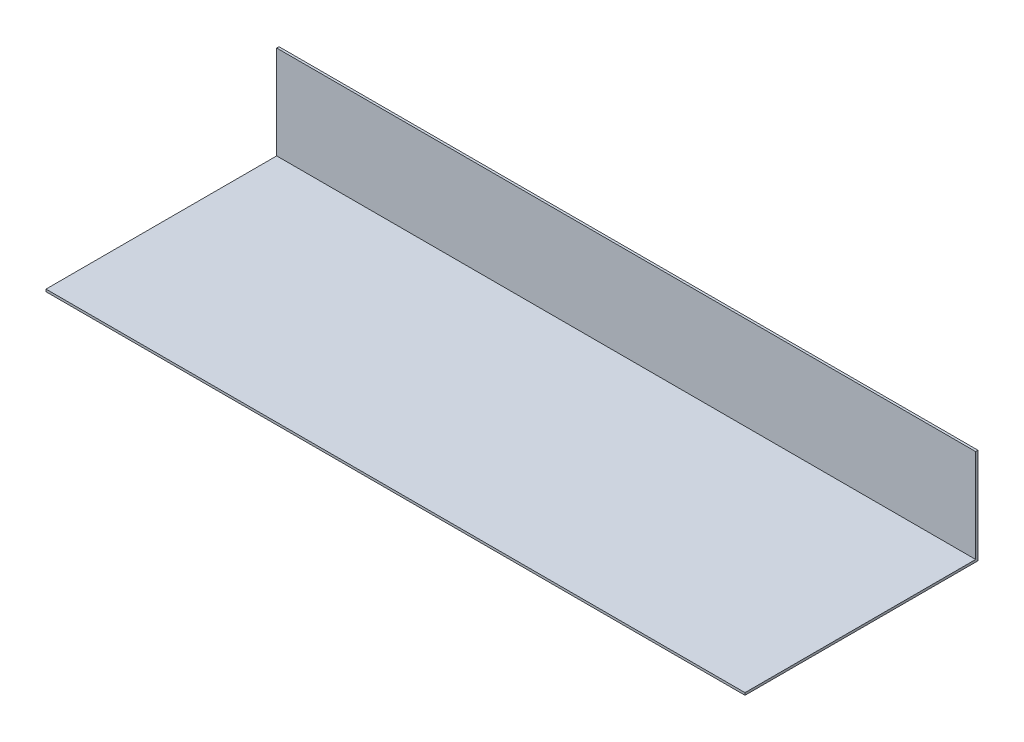
SolidWorks part; units mm, degrees
ref_plane "Front Plane" through (0, 0, 0) normal (0, 0, 1) x (1, 0, 0)
ref_plane "Top Plane" through (0, 0, 0) normal (0, 1, 0) x (1, 0, 0)
ref_plane "Right Plane" through (0, 0, 0) normal (1, 0, 0) x (0, 0, -1)
sketch "Sketch2" plane through (0, 0, 0) normal (0, 1, 0) x (1, 0, 0)
  line L1 (-450, 150) -> (450, 150)
  line L2 (-450, 150) -> (-450, -150)
  line L3 (-450, -150) -> (450, -150)
  line L4 (450, 150) -> (450, -150)
  line L5 (-450, 150) -> (450, -150) construction
  line L6 (-450, -150) -> (450, 150) construction
  point P0 (0, 0)
  dimension "D1" = 300
  dimension "D2" = 900
extrude "Boss-Extrude1" add sketch "Sketch2" along normal blind 3
sketch "Sketch3" plane through (0, 3, 0) normal (0, 1, 0) x (1, 0, 0)
  line L0 (450, -150) -> (450, 150) construction
  line L1 (-450, 150) -> (450, 150)
  line L2 (-450, 150) -> (-450, 147)
  line L3 (-450, 147) -> (450, 147)
  line L4 (450, 150) -> (450, 147)
  dimension "D1" = 3
extrude "Boss-Extrude2" add sketch "Sketch3" along normal blind 120.3
sketch "Base Plate Placement" plane through (0, 3, 0) normal (0, 1, 0) x (1, 0, 0)
  line L1 (-100, -100) -> (100, -100)
  line L2 (-100, -100) -> (-100, 100)
  line L3 (-100, 100) -> (100, 100)
  line L4 (100, -100) -> (100, 100)
  line L5 (-100, -100) -> (100, 100) construction
  line L6 (-100, 100) -> (100, -100) construction
  circle A0 centre (0, 0) radius 51.65
  point P0 (0, 0)
  dimension "D2" = 103.3
  dimension "D1" = 200
